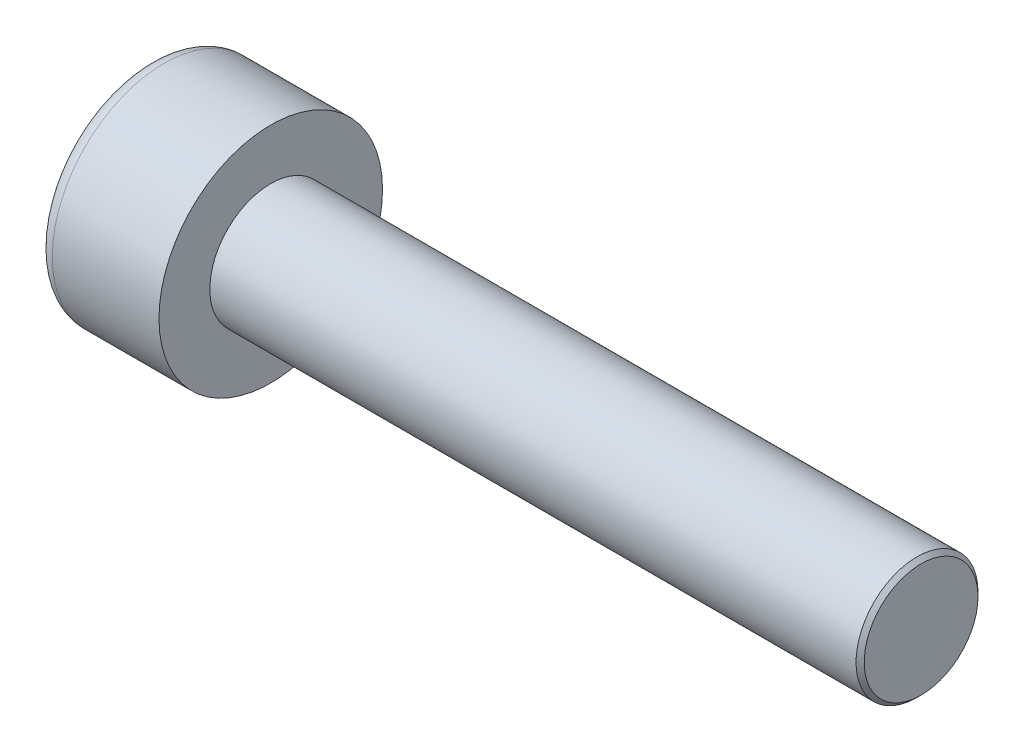
SolidWorks part; units mm, degrees
ref_plane "Front" through (0, 0, 0) normal (0, 0, 1) x (1, 0, 0)
ref_plane "Top" through (0, 0, 0) normal (0, 1, 0) x (1, 0, 0)
ref_plane "Right" through (0, 0, 0) normal (1, 0, 0) x (0, 0, -1)
other "Configuration Table"
sketch "Sketch1" plane through (0, 0, 0) normal (1, 0, 0) x (0, 0, -1)
  circle A0 centre (0, 0) radius 2.75
  dimension "dk" = 5.5
extrude "BaseHead" add sketch "Sketch1" along normal blind 3
sketch "Sketch2" plane through (3, 0, 0) normal (1, 0, 0) x (0, 0, -1)
  circle A0 centre (0, 0) radius 1.5
  dimension "d" = 3
extrude "BaseBody" add sketch "Sketch2" along normal blind 16
cosmetic thread "ThreadCosmetic1" [suppressed] parameters "b"=16, "D2"=2.459
sketch "Sketch3" plane through (0, 0, 0) normal (1, 0, 0) x (0, 0, -1)
  line L1 (1.4434, 0) -> (0.7217, 1.25)
  line L2 (0.7217, 1.25) -> (-0.7217, 1.25)
  line L3 (-0.7217, 1.25) -> (-1.4434, 0)
  line L4 (-1.4434, 0) -> (-0.7217, -1.25)
  line L5 (-0.7217, -1.25) -> (0.7217, -1.25)
  line L6 (0.7217, -1.25) -> (1.4434, 0)
  circle A0 centre (0, 0) radius 1.25 construction
  dimension "s" = 2.5
  dimension "e" = 2.8868
extrude "HexagonSocket" cut sketch "Sketch3" along normal blind 1.3
sketch "Sketch4" plane through (-4.1961, 0.75, 0) normal (0, 0, 1) x (-1, 0, 0)
  line L0 (-5.4961, 2) -> (-6.2178, 0.75)
  line L2 (-6.2178, 0.75) -> (-5.4961, 0.75)
  line L3 (-5.4961, 0.75) -> (-5.4961, 2)
  line L4 (-5.0351, 0.75) -> (0.839, 0.75) construction
  line L5 (-23.1961, 0.75) -> (-7.1961, 0.75) construction
  line L6 (-7.1961, 0.75) -> (-4.1961, 0.75) construction
  dimension "m" = 60
revolve "Cut-Revolve1" cut sketch "Sketch4" angle 360 about L4
fillet "HeadFillet" [suppressed] radius 0.1
fillet "TopFillet" radius 0.375 1 edges at (0, 0, -2.75)
chamfer "Chamfer1" distance 0.1 angle 45 1 edges at (19, 0, -1.5)
sketch "Sketch5" plane through (0, 0, 0) normal (0, 0, 1) x (1, 0, 0)
  line L0 (18.9, 1.2657) -> (19.0353, 1.5)
  line L1 (19.0353, 1.5) -> (19.0353, 1.7705)
  line L2 (19.0353, 1.7705) -> (18.7647, 1.7705)
  line L3 (18.7647, 1.7705) -> (18.7647, 1.5)
  line L4 (18.7647, 1.5) -> (18.9, 1.2657)
  line L5 (0, 0) -> (7.8886, 0) construction
  line L6 (18.9, -1.5) -> (18.9, 1.5) construction
  dimension "D1" = 3
  dimension "D2" = 0.2705
revolve "Cut-Revolve10" [suppressed] cut sketch "Sketch5" angle 360 about L5
pattern_linear "LPattern10" [suppressed] count 49 spacing 0.3246 along (1, 0, 0)
equation "\"r1@TopFillet\" = \"d@Sketch2\" / 8"
equation "\"D1@Chamfer1\" = \"r@HeadFillet\""
equation "\"D1@Sketch5\" = \"d@Sketch2\""
equation "\"D2@Sketch5\" =  ( \"d@Sketch2\" - \"D2@ThreadCosmetic1\" )  / 2"
equation "\"D3@LPattern10\" = \"D2@Sketch5\" * 1.2"
equation "\"D1@LPattern10\" = \"b@ThreadCosmetic1\" / \"D3@LPattern10\""
